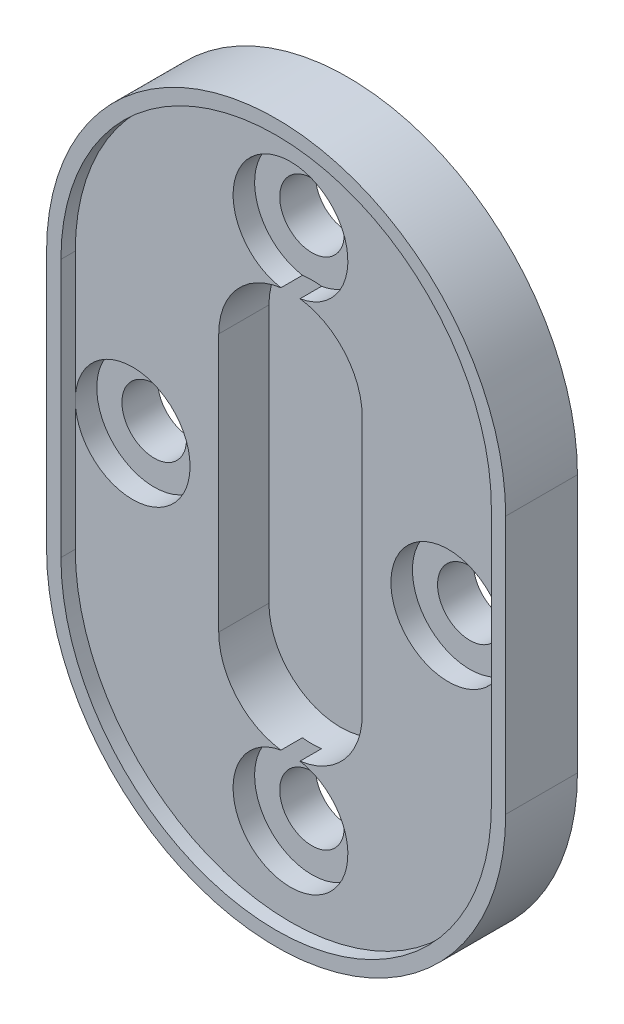
SolidWorks part; units mm, degrees
ref_plane "Front Plane" through (0, 0, 0) normal (0, 0, 1) x (1, 0, 0)
ref_plane "Top Plane" through (0, 0, 0) normal (0, 1, 0) x (1, 0, 0)
ref_plane "Right Plane" through (0, 0, 0) normal (1, 0, 0) x (0, 0, -1)
sketch "Sketch1" plane through (0, 0, 0) normal (0, 0, 1) x (1, 0, 0)
  line L0 (0, -9) -> (0, 9) construction
  line L1 (-16, -9) -> (-16, 9)
  line L2 (16, -9) -> (16, 9)
  arc A0 (-16, -9) -> (16, -9) centre (0, -9) ccw
  arc A1 (16, 9) -> (-16, 9) centre (0, 9) ccw
  point P2 (0, 0)
  point P8 (0, 25)
  point P9 (0, -25)
  dimension "D1" = 32
  dimension "D2" = 50
extrude "Boss-Extrude1" add sketch "Sketch1" along normal blind 4
sketch "Sketch2" plane through (0, 0, 4) normal (0, 0, 1) x (1, 0, 0)
  line L0 (0, -9) -> (0, 9) construction
  line L1 (-5, -9) -> (-5, 9)
  line L2 (5, -9) -> (5, 9)
  arc A0 (-5, -9) -> (5, -9) centre (0, -9) ccw
  arc A1 (5, 9) -> (-5, 9) centre (0, 9) ccw
  point P2 (0, 0)
  point P8 (0, 14)
  point P9 (0, -14)
  dimension "D1" = 28
  dimension "D2" = 10
extrude "Cut-Extrude1" cut sketch "Sketch2" against normal blind 3.5
sketch "Sketch3" plane through (0, 0, 4) normal (0, 0, 1) x (1, 0, 0)
  line L2 (16, -9) -> (16, 9) construction
  line L3 (-16, 9) -> (-16, -9) construction
  line L4 (-15, 9) -> (-15, -9)
  line L5 (15, -9) -> (15, 9)
  line L6 (-15, 9) -> (-15, -9)
  line L7 (15, -9) -> (15, 9)
  line L8 (16, -9) -> (16, 9)
  line L9 (-16, 9) -> (-16, -9)
  arc A3 (-16, -9) -> (16, -9) centre (0, -9) ccw construction
  arc A4 (16, 9) -> (-16, 9) centre (0, 9) ccw construction
  arc A5 (-15, -9) -> (15, -9) centre (0, -9) ccw
  arc A6 (15, 9) -> (-15, 9) centre (0, 9) ccw
  arc A7 (-15, -9) -> (15, -9) centre (0, -9) ccw
  arc A8 (15, 9) -> (-15, 9) centre (0, 9) ccw
  arc A9 (-16, -9) -> (16, -9) centre (0, -9) ccw
  arc A10 (16, 9) -> (-16, 9) centre (0, 9) ccw
  dimension "D1" = 1
extrude "Boss-Extrude2" add sketch "Sketch3" along normal blind 1
hole_wizard "CBORE for M5 Hex Head Bolt1" positions "Sketch4" profile "Sketch5" counterbore size "M5" standard "ISO" end condition up to next
sketch "Sketch4" plane through (0, 0, 4) normal (0, 0, 1) x (1, 0, 0)
  line L0 (-11, 0) -> (11, 0) construction
  line L2 (0, 17.9) -> (0, -17.9) construction
  point P0 (0, 17.9)
  point P2 (11, 0)
  point P4 (-11, 0)
  point P6 (0, -17.9)
  point P26 (0, 0)
  point P28 (0, 0)
sketch "Sketch5" plane through (0, 17.9, 4) normal (1, 0, 0) x (0, -1, 0)
  line L0 (0, 0) -> (0, 4)
  line L1 (0, 4) -> (2.25, 4)
  line L3 (2.25, 4) -> (2.25, 1.5)
  line L4 (2.25, 1.5) -> (4, 1.5)
  line L5 (4, 1.5) -> (4, 0)
  line L7 (4, 0) -> (0, 0)
  line L11 (0, -6.35) -> (0, 107.95) construction
  dimension "Thru Hole Dia." = 4.5
  dimension "Thru Hole Depth" = 4
  dimension "C'Bore Dia." = 8
  dimension "C'Bore Depth" = 1.5
